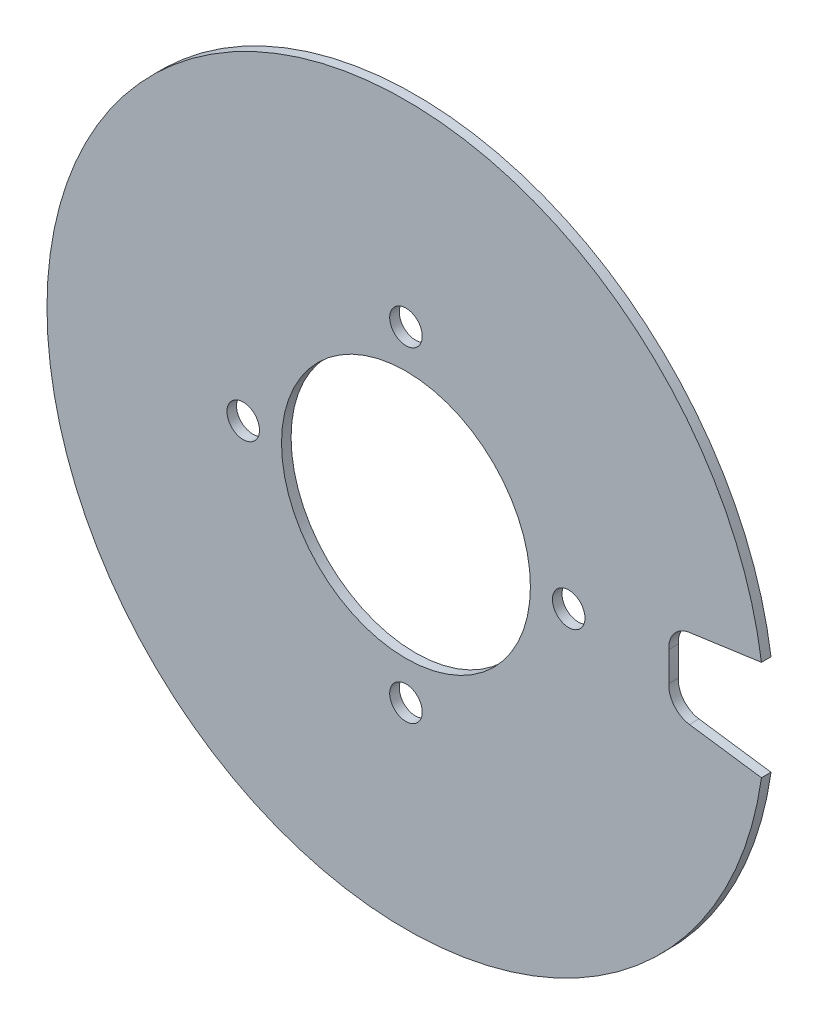
SolidWorks part; units mm, degrees
ref_plane "Front Plane" through (0, 0, 0) normal (0, 0, 1) x (1, 0, 0)
ref_plane "Top Plane" through (0, 0, 0) normal (0, 1, 0) x (1, 0, 0)
ref_plane "Right Plane" through (0, 0, 0) normal (1, 0, 0) x (0, 0, -1)
sketch "Sketch1" plane through (0, 0, 0) normal (0, 0, 1) x (1, 0, 0)
  circle A0 centre (0, 0) radius 37.5
extrude "Boss-Extrude1" add sketch "Sketch1" along normal blind 1 contours A0
sketch "Sketch2" plane through (0, 0, 1) normal (0, 0, 1) x (1, 0, 0)
  circle A0 centre (0, 0) radius 13
extrude "Cut-Extrude1" cut sketch "Sketch2" against normal through all
sketch "Sketch3" plane through (0, 0, 1) normal (0, 0, 1) x (1, 0, 0)
  point P0 (0, 17)
  point P2 (17, 0)
  point P4 (0, -17)
  point P6 (-17, 0)
  point P9 (0, 0)
  point P10 (0, 0)
  point P11 (0, 0)
  point P12 (0, 0)
hole_wizard "Tap Drill for M3x0.5 Tap1" positions "Sketch3" profile "Sketch4" hole size "M3x0.5" standard "JIS" end condition through all
sketch "Sketch4" plane through (0, 17, 1) normal (1, 0, 0) x (0, -1, 0)
  line L0 (0, 0) -> (0, 1)
  line L1 (0, 1) -> (1.7, 1)
  line L2 (1.7, 1) -> (1.7, 0)
  line L5 (1.7, 0) -> (0, 0)
  line L11 (0, -6.35) -> (0, 107.95) construction
  dimension "Thru Hole Dia." = 3.4
  dimension "Thru Hole Depth" = 1
sketch "Sketch5" plane through (0, 0, 1) normal (0, 0, 1) x (1, 0, 0)
  line L0 (27.2324, 3.8273) -> (37.1351, 5.219)
  line L1 (27.2324, -3.8273) -> (37.1351, -5.219)
  arc A0 (27.2324, -3.8273) -> (27.2324, 3.8273) centre (0, 0) ccw
  arc A1 (37.1351, -5.219) -> (37.1351, 5.219) centre (0, 0) ccw
extrude "Cut-Extrude2" cut sketch "Sketch5" against normal through all
fillet "Fillet1" radius 2.5 2 edges at (27.2324, -3.8273, 0.5) (27.2324, 3.8273, 0.5)
